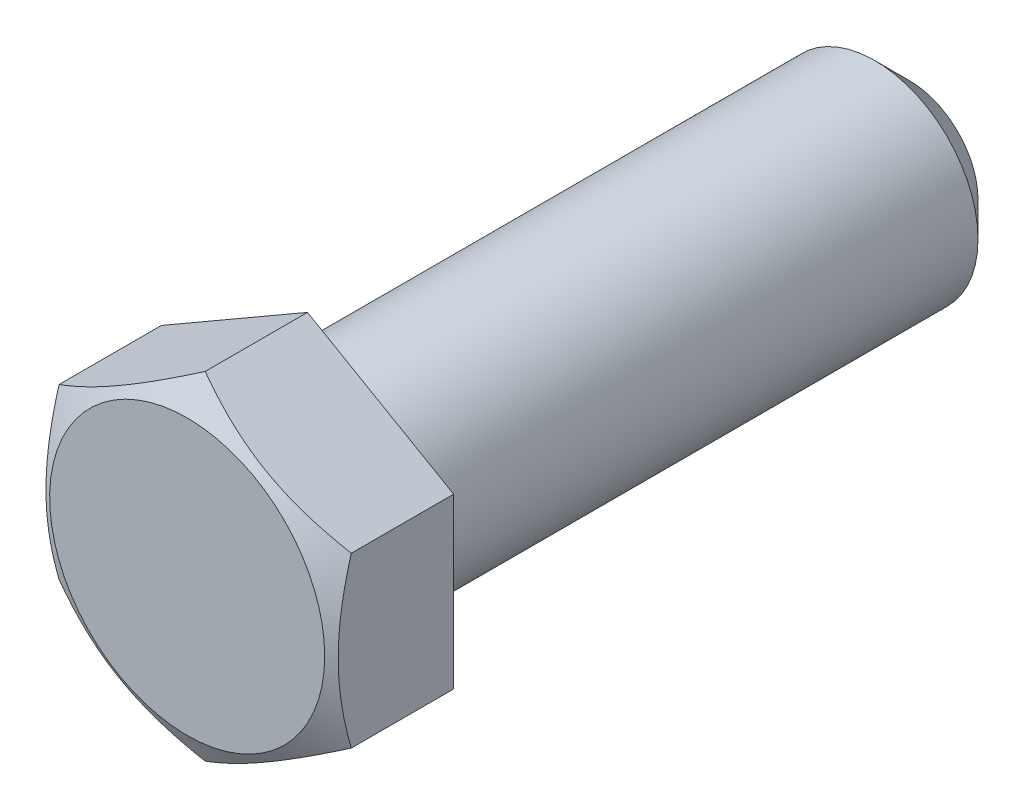
SolidWorks part; units mm, degrees
material "Сталь 35 ГОСТ 1050-2013"
ref_plane "Спереди" through (0, 0, 0) normal (0, 0, 1) x (1, 0, 0)
ref_plane "Сверху" through (0, 0, 0) normal (0, 1, 0) x (1, 0, 0)
ref_plane "Справа" through (0, 0, 0) normal (1, 0, 0) x (0, 0, -1)
sketch "Эскиз1" plane through (0, 0, 0) normal (1, 0, 0) x (0, 0, -1)
  line L0 (0, 0) -> (42, 0) construction
  line L1 (0, 0) -> (0, 10)
  line L2 (0, 10) -> (7, 10)
  line L3 (7, 10) -> (7, 6)
  line L4 (7, 6) -> (42, 6)
  line L5 (42, 6) -> (42, 0)
  line L6 (0, 8) -> (1.1547, 10)
  dimension "D1" = 20
  dimension "D2" = 7
  dimension "D3" = 35
  dimension "D4" = 12
  dimension "D5" = 30
  dimension "D6" = 16
revolve "Повернуть2" add sketch "Эскиз1" angle 360 about L0
cosmetic thread "Условное изображение резьбы2" parameters "D1"=30, "D2"=8
chamfer "Фаска2" distance 2 angle 45 1 edges at (6, 0, -42)
fillet "Скругление2" radius 0.6 1 edges at (6, 0, -7)
sketch "Эскиз7" plane through (0, 0, 0) normal (0, 0, 1) x (1, 0, 0)
  line L7 (0, 9.815) -> (-8.5, 4.9075)
  line L8 (-8.5, 4.9075) -> (-8.5, -4.9075)
  line L9 (-8.5, -4.9075) -> (0, -9.815)
  line L10 (0, -9.815) -> (8.5, -4.9075)
  line L11 (8.5, -4.9075) -> (8.5, 4.9075)
  line L12 (8.5, 4.9075) -> (0, 9.815)
  circle A0 centre (0, 0) radius 8.5 construction
  dimension "D1" = 17
extrude "Вырез-Вытянуть5" cut sketch "Эскиз7" against normal blind 7 flip side to cut
